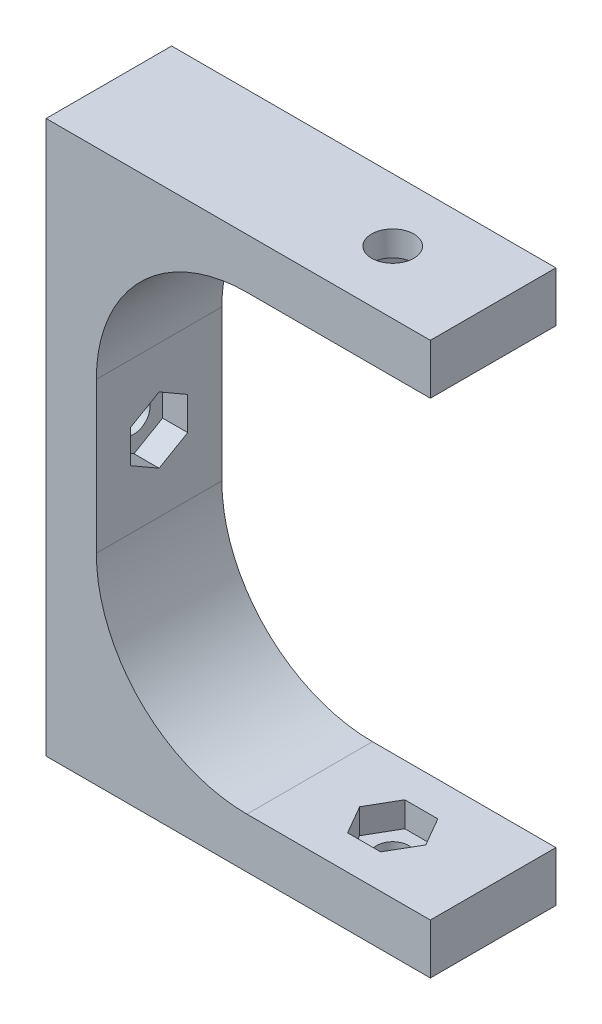
SolidWorks part; units mm, degrees
ref_plane "Front Plane" through (0, 0, 0) normal (0, 0, 1) x (1, 0, 0)
ref_plane "Top Plane" through (0, 0, 0) normal (0, 1, 0) x (1, 0, 0)
ref_plane "Right Plane" through (0, 0, 0) normal (1, 0, 0) x (0, 0, -1)
sketch "Sketch1" plane through (0, 0, 0) normal (0, 0, 1) x (1, 0, 0)
  line L0 (38.2667, 27.5) -> (38.2667, 22.5)
  line L1 (38.2667, 22.5) -> (5, 22.5)
  line L2 (5, 22.5) -> (5, -22.5)
  line L3 (5, -22.5) -> (38.2667, -22.5)
  line L4 (38.2667, -22.5) -> (38.2667, -27.5)
  line L5 (38.2667, -27.5) -> (0, -27.5)
  line L6 (0, -27.5) -> (0, 27.5)
  line L7 (0, 27.5) -> (38.2667, 27.5)
  line L8 (-239.5134, 0) -> (11736.1573, 0) construction
  point P2 (0, 0)
  point P11 (28.2667, 22.5)
  dimension "D1" = 5
  dimension "D2" = 5
  dimension "D3" = 55
  dimension "D4" = 28.2667
  dimension "D5" = 10
extrude "Boss-Extrude1" add sketch "Sketch1" along normal blind 12.5
fillet "Fillet1" radius 15 2 edges at (5, -22.5, 6.25) (5, 22.5, 6.25)
sketch "Sketch2" plane through (0, 27.5, 0) normal (0, 1, 0) x (1, 0, 0)
  line L0 (38.2667, -12.5) -> (38.2667, 0) construction
  circle A0 centre (28.2667, -6.25) radius 2.1
  point P5 (38.2667, -6.25)
  dimension "D2" = 4.2
  dimension "D1" = 10
extrude "Cut-Extrude1" cut sketch "Sketch2" against normal up to surface (5 mm away) up to face at (29.1333, 22.5, 6.25)
sketch "Sketch3" plane through (0, 22.5, 0) normal (0, -1, 0) x (1, 0, 0)
  line L1 (30.3451, 9.85) -> (26.1882, 9.85)
  line L2 (26.1882, 9.85) -> (24.1097, 6.25)
  line L3 (24.1097, 6.25) -> (26.1882, 2.65)
  line L4 (26.1882, 2.65) -> (30.3451, 2.65)
  line L5 (30.3451, 2.65) -> (32.4236, 6.25)
  line L6 (32.4236, 6.25) -> (30.3451, 9.85)
  circle A0 centre (28.2667, 6.25) radius 3.6 construction
  dimension "D1" = 7.2
extrude "Cut-Extrude2" cut sketch "Sketch3" against normal blind 2.5
sketch "Sketch4" plane through (0, -22.5, 0) normal (0, 1, 0) x (1, 0, 0)
  line L0 (38.2667, -12.5) -> (38.2667, 0) construction
  circle A0 centre (28.2667, -6.25) radius 1.6
  point P4 (38.2667, -6.25)
  dimension "D2" = 3.2
  dimension "D1" = 10
extrude "Cut-Extrude3" cut sketch "Sketch4" against normal blind 5
sketch "Sketch5" plane through (0, -22.5, 0) normal (0, 1, 0) x (1, 0, 0)
  line L1 (29.9121, -3.4) -> (26.6212, -3.4)
  line L2 (26.6212, -3.4) -> (24.9758, -6.25)
  line L3 (24.9758, -6.25) -> (26.6212, -9.1)
  line L4 (26.6212, -9.1) -> (29.9121, -9.1)
  line L5 (29.9121, -9.1) -> (31.5576, -6.25)
  line L6 (31.5576, -6.25) -> (29.9121, -3.4)
  circle A0 centre (28.2667, -6.25) radius 2.85 construction
  dimension "D1" = 5.7
extrude "Cut-Extrude4" cut sketch "Sketch5" against normal blind 2.5
sketch "Sketch6" plane through (38.2667, 0, 0) normal (1, 0, 0) x (0, 0, -1)
  line L0 (0, 7.5) -> (-12.5, 7.5) construction
  circle A0 centre (-6.25, 0) radius 1.6
  point P6 (-6.25, 7.5)
  dimension "D1" = 3.2
extrude "Cut-Extrude5" cut sketch "Sketch6" against normal through all
sketch "Sketch7" plane through (5, 0, 0) normal (1, 0, 0) x (0, 0, -1)
  line L1 (-3.4, -1.6454) -> (-3.4, 1.6454)
  line L2 (-3.4, 1.6454) -> (-6.25, 3.2909)
  line L3 (-6.25, 3.2909) -> (-9.1, 1.6454)
  line L4 (-9.1, 1.6454) -> (-9.1, -1.6454)
  line L5 (-9.1, -1.6454) -> (-6.25, -3.2909)
  line L6 (-6.25, -3.2909) -> (-3.4, -1.6454)
  circle A0 centre (-6.25, 0) radius 2.85 construction
  dimension "D1" = 5.7
extrude "Cut-Extrude6" cut sketch "Sketch7" against normal blind 2.5
equation "\"D4@Sketch1\"=16.6+(100/6)-5"
